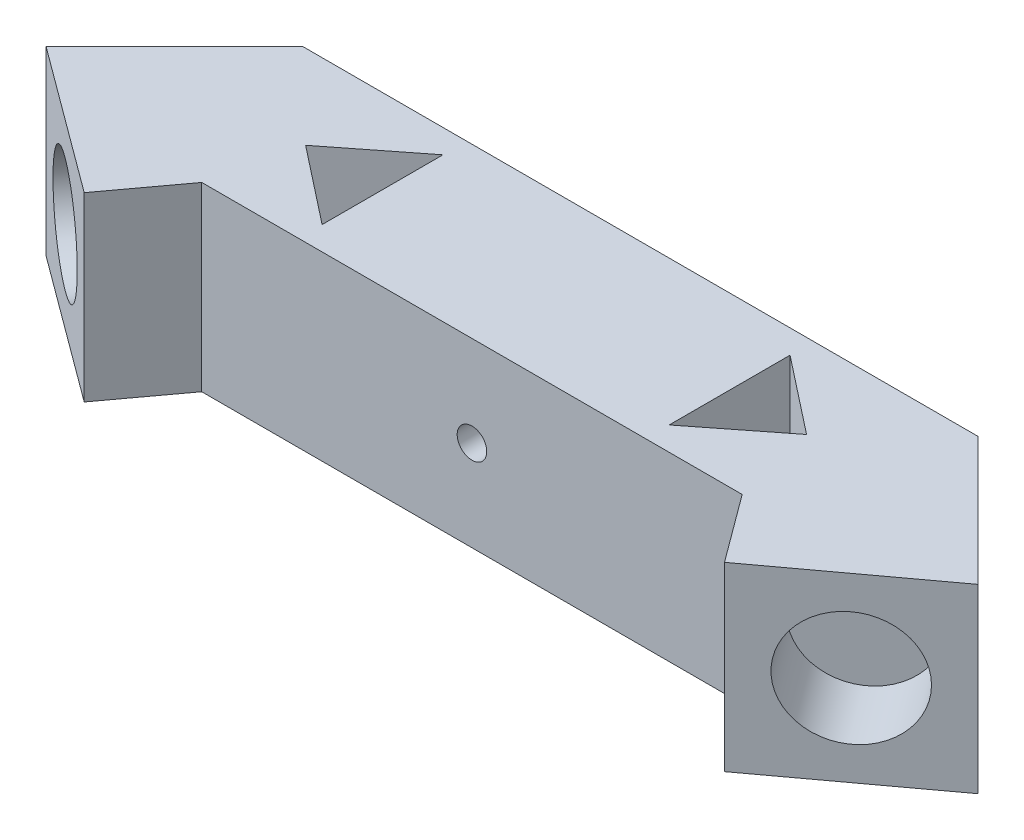
SolidWorks part; units mm, degrees
ref_plane "Front Plane" through (0, 0, 0) normal (0, 0, 1) x (1, 0, 0)
ref_plane "Top Plane" through (0, 0, 0) normal (0, 1, 0) x (1, 0, 0)
ref_plane "Right Plane" through (0, 0, 0) normal (1, 0, 0) x (0, 0, -1)
sketch "Sketch1" plane through (0, 0, 0) normal (0, 1, 0) x (1, 0, 0)
  line L1 (0, 0) -> (113.5797, 0)
  line L3 (-14.2032, 35.3536) -> (127.7828, 35.3536)
  line L5 (0, 0) -> (-10.4888, -14.2118)
  line L6 (-41.1439, 8.4129) -> (-10.4888, -14.2118)
  line L7 (56.7898, 35.3536) -> (56.7898, 0) construction
  line L8 (113.5797, 0) -> (124.0685, -14.2118)
  line L9 (154.7236, 8.4129) -> (124.0685, -14.2118)
  line L10 (127.7828, 35.3536) -> (154.7236, 8.4129)
  line L11 (-14.2032, 35.3536) -> (-41.1439, 8.4129)
  dimension "D1" = 141.986
  dimension "D2" = 135
  dimension "D3" = 38.1
  dimension "D4" = 38.1
  dimension "D5" = 10.4888
  dimension "D6" = 38.1
extrude "Boss-Extrude1" add sketch "Sketch1" along normal blind 38.1
sketch "Sketch2" plane through (-10.4888, 0, 14.2118) normal (-0.5938, 0, 0.8046) x (0.8046, 0, 0.5938)
  line L0 (-38.1, 38.1) -> (0, 0) construction
  line L1 (-38.1, 0) -> (0, 38.1) construction
  circle A0 centre (-19.05, 19.05) radius 12.065
  dimension "D1" = 24.13
extrude "Cut-Extrude1" cut sketch "Sketch2" against normal blind 15.24
sketch "Sketch3" plane through (50.5399, 0, 68.4787) normal (0.5938, 0, 0.8046) x (0.8046, 0, -0.5938)
  line L0 (91.3857, 38.1) -> (129.4857, 0) construction
  line L1 (91.3857, 0) -> (129.4857, 38.1) construction
  circle A0 centre (110.4357, 19.05) radius 12.065
  point P11 (110.4357, 19.05)
  dimension "D1" = 24.13
extrude "Cut-Extrude2" cut sketch "Sketch3" against normal blind 15.24
sketch "Sketch5" plane through (0, 38.1, 0) normal (0, 1, 0) x (1, 0, 0)
  line L0 (56.7898, 35.3536) -> (56.7898, 0) construction
  line L1 (127.7828, 35.3536) -> (-14.2032, 35.3536) construction
  line L2 (0, 0) -> (113.5797, 0) construction
  line L3 (2.7565, 17.6768) -> (45.3845, 17.6768) construction
  line L4 (4.1516, 17.6768) -> (20.32, 30.3768)
  line L5 (20.32, 30.3768) -> (20.32, 4.9768)
  line L6 (20.32, 4.9768) -> (4.1516, 17.6768)
  line L7 (32.8523, 35.3536) -> (32.8523, 0) construction
  line L13 (93.2597, 30.3768) -> (93.2597, 4.9768)
  line L14 (109.4281, 17.6768) -> (93.2597, 30.3768)
  line L15 (93.2597, 4.9768) -> (109.4281, 17.6768)
  line L19 (68.1951, 17.6768) -> (110.8231, 17.6768) construction
  dimension "D1" = 25.4
  dimension "D2" = 32.8523
  dimension "D3" = 38.149
  dimension "D4" = 20.32
  dimension "D5" = 42.628
  dimension "D6" = 42.628
  dimension "D7" = 17.6768
extrude "Cut-Extrude3" cut sketch "Sketch5" against normal blind 38.1
sketch "Sketch6" plane through (0, 0, -35.3536) normal (0, 0, -1) x (-1, 0, 0)
  line L0 (-56.7898, 38.1) -> (-56.7898, 0) construction
  line L1 (-127.7828, 38.1) -> (14.2032, 38.1) construction
  line L2 (-127.7828, 0) -> (14.2032, 0) construction
  line L3 (-127.7828, 19.05) -> (14.2032, 19.05) construction
  line L4 (-127.7828, 38.1) -> (-127.7828, 0) construction
  line L5 (14.2032, 38.1) -> (14.2032, 0) construction
  circle A0 centre (-56.7898, 19.05) radius 3.1115
  dimension "D1" = 6.223
extrude "Cut-Extrude4" cut sketch "Sketch6" against normal blind 46.482
